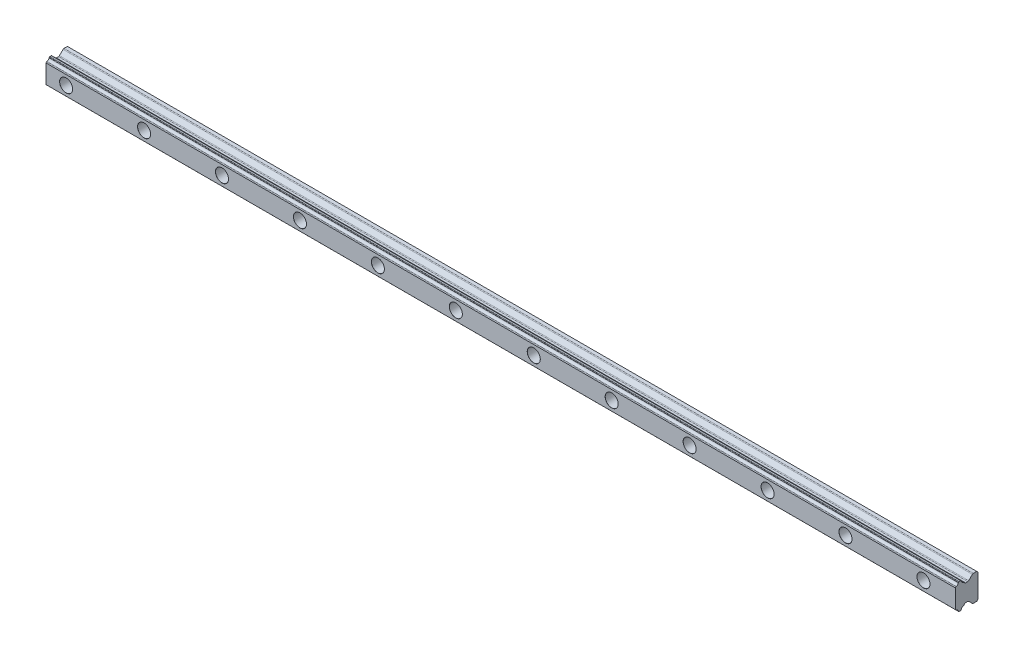
SolidWorks part; units mm, degrees
material "Plain Carbon Steel"
ref_plane "Front Plane" through (0, 0, 0) normal (0, 0, 1) x (1, 0, 0)
ref_plane "Top Plane" through (0, 0, 0) normal (0, 1, 0) x (1, 0, 0)
ref_plane "Right Plane" through (0, 0, 0) normal (1, 0, 0) x (0, 0, -1)
sketch3d "3DSketch1"
  line L0 (350, 0, 0) -> (-350, 0, 0)
  point P4 (0, 0, 0)
  dimension "D1" = 700
ref_plane "Plane1" through (350, 0, 0) normal (-1, 0, 0) x (0, -0.7071, 0.7071)
other "Hgr HGR20(1)"
ref_plane "Plane3" through (350, 0, 0) normal (-1, 0, 0) x (0, -1, 0)
sketch "Sketch14" plane through (350, 0, 0) normal (-1, 0, 0) x (0, -1, 0)
  line L0 (-9, 0) -> (9, 0)
  line L1 (9, 0) -> (10, 1)
  line L2 (10, 1) -> (10, 3.6565)
  line L3 (9.7071, 4.3636) -> (6.8929, 7.1778)
  line L4 (6.6, 7.8849) -> (6.6, 9.4451)
  line L5 (6.8929, 10.1522) -> (7.6302, 10.8894)
  line L6 (9.6906, 12.9499) -> (9.8536, 13.1128)
  line L7 (10, 13.4664) -> (10, 14.5236)
  line L8 (9.8536, 14.8772) -> (9.6785, 15.0522)
  line L9 (7.6325, 17.0982) -> (7.2307, 17.5)
  line L10 (7.2307, 17.5) -> (-7.2307, 17.5)
  line L11 (-7.2307, 17.5) -> (-7.6325, 17.0982)
  line L12 (-9.6785, 15.0522) -> (-9.8536, 14.8772)
  line L13 (-10, 14.5236) -> (-10, 13.4664)
  line L14 (-9.8536, 13.1128) -> (-9.6906, 12.9499)
  line L15 (-7.6302, 10.8894) -> (-6.8929, 10.1522)
  line L16 (-6.6, 9.4451) -> (-6.6, 7.8849)
  line L17 (-6.8929, 7.1778) -> (-9.7071, 4.3636)
  line L18 (-10, 3.6565) -> (-10, 1)
  line L19 (-10, 1) -> (-9, 0)
  arc A0 (10, 3.6565) -> (9.7071, 4.3636) centre (9, 3.6565) ccw
  arc A1 (6.6, 7.8849) -> (6.8929, 7.1778) centre (7.6, 7.8849) ccw
  arc A2 (6.8929, 10.1522) -> (6.6, 9.4451) centre (7.6, 9.4451) ccw
  arc A3 (7.6302, 10.8894) -> (7.8468, 11.2275) centre (7.3529, 11.3055) ccw
  arc A4 (9.4318, 12.8125) -> (7.8468, 11.2275) centre (9.8106, 10.8487) ccw
  arc A5 (9.4318, 12.8125) -> (9.6906, 12.9499) centre (9.3371, 13.3035) ccw
  arc A6 (9.8536, 13.1128) -> (10, 13.4664) centre (9.5, 13.4664) ccw
  arc A7 (10, 14.5236) -> (9.8536, 14.8772) centre (9.5, 14.5236) ccw
  arc A8 (9.6785, 15.0522) -> (9.422, 15.1892) centre (9.3249, 14.6987) ccw
  arc A9 (7.8482, 16.763) -> (9.422, 15.1892) centre (9.8101, 17.1511) ccw
  arc A10 (7.8482, 16.763) -> (7.6325, 17.0982) centre (7.3547, 16.6825) ccw
  arc A11 (-7.6325, 17.0982) -> (-7.8482, 16.763) centre (-7.3547, 16.6825) ccw
  arc A12 (-9.422, 15.1892) -> (-7.8482, 16.763) centre (-9.8101, 17.1511) ccw
  arc A13 (-9.422, 15.1892) -> (-9.6785, 15.0522) centre (-9.3249, 14.6987) ccw
  arc A14 (-9.8536, 14.8772) -> (-10, 14.5236) centre (-9.5, 14.5236) ccw
  arc A15 (-10, 13.4664) -> (-9.8536, 13.1128) centre (-9.5, 13.4664) ccw
  arc A16 (-9.6906, 12.9499) -> (-9.4318, 12.8125) centre (-9.3371, 13.3035) ccw
  arc A17 (-7.8468, 11.2275) -> (-9.4318, 12.8125) centre (-9.8106, 10.8487) ccw
  arc A18 (-7.8468, 11.2275) -> (-7.6302, 10.8894) centre (-7.3529, 11.3055) ccw
  arc A19 (-6.6, 9.4451) -> (-6.8929, 10.1522) centre (-7.6, 9.4451) ccw
  arc A20 (-6.8929, 7.1778) -> (-6.6, 7.8849) centre (-7.6, 7.8849) ccw
  arc A21 (-9.7071, 4.3636) -> (-10, 3.6565) centre (-9, 3.6565) ccw
  point P64 (0, 0)
hole_wizard "CBORE for M5 Hex Socket Head Cap Screw1" positions "Sketch15" profile "Sketch16" counterbore size "M5" standard "DIN" end condition up to next
sketch "Sketch15" plane through (0, 0, 17.5) normal (0, 0, 1) x (1, 0, 0)
  line L0 (-350, -7.2307) -> (-350, 7.2307) construction
  point P0 (-334.5, 0)
  dimension "D1" = 15.5
sketch "Sketch16" plane through (-334.5, 0, 17.5) normal (1, 0, 0) x (0, -1, 0)
  line L0 (0, 0) -> (0, 17.5)
  line L1 (0, 17.5) -> (2.9, 17.5)
  line L3 (2.9, 17.5) -> (2.9, 8.5)
  line L4 (5, 8.5) -> (2.9, 8.5)
  line L5 (5, 8.5) -> (5, 0.025)
  line L6 (5, 0.025) -> (5.025, 0)
  line L7 (5.025, 0) -> (0, 0)
  line L8 (-5, 0.025) -> (-5.025, 0) construction
  line L11 (0, -6.35) -> (0, 107.95) construction
  dimension "Thru Hole Dia." = 5.8
  dimension "Thru Hole Depth" = 17.5
  dimension "C'Bore Dia." = 10
  dimension "C'Bore Depth" = 8.5
  dimension "Near C'Sink Dia." = 10.05
  dimension "Near C'Sink Angle" = 90
pattern_linear "LPattern1" count 12 spacing 60 along (1, 0, 0) of "CBORE for M5 Hex Socket Head Cap Screw1"
